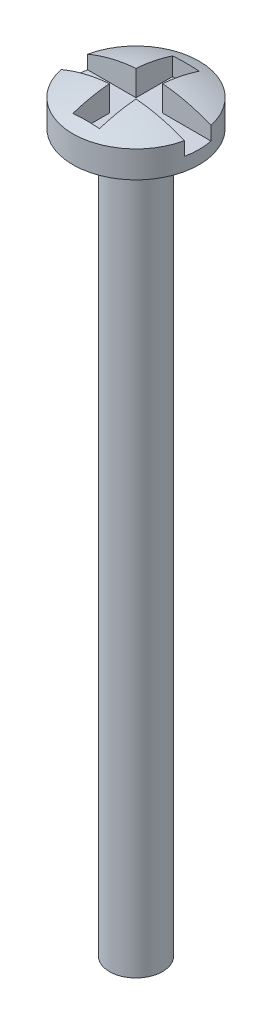
SolidWorks part; units mm, degrees
ref_plane "前视基准面" through (0, 0, 0) normal (0, 0, 1) x (1, 0, 0)
ref_plane "上视基准面" through (0, 0, 0) normal (0, 1, 0) x (1, 0, 0)
ref_plane "右视基准面" through (0, 0, 0) normal (1, 0, 0) x (0, 0, -1)
sketch "草图1" plane through (0, 0, 0) normal (0, 1, 0) x (1, 0, 0)
  circle A0 centre (0, 0) radius 1
  dimension "D1" = 2
extrude "拉伸1" add sketch "草图1" along normal blind 27
sketch "草图2" plane through (0, 27, 0) normal (0, 1, 0) x (-1, 0, 0)
  circle A0 centre (0, 0) radius 2.375
  dimension "D1" = 4.75
extrude "拉伸2" add sketch "草图2" along normal blind 1.5
sketch "草图3" plane through (0, 28.5, 0) normal (0, 1, 0) x (-1, 0, 0)
  line L0 (4.0624, 0) -> (-4.2778, 0) construction
  line L1 (0, -3.5166) -> (0, 3.738) construction
  line L3 (3.5023, -0.5) -> (-3.5023, -0.5)
  line L4 (3.5023, -0.5) -> (3.5023, 0.5)
  line L5 (3.5023, 0.5) -> (-3.5023, 0.5)
  line L6 (-3.5023, -0.5) -> (-3.5023, 0.5)
  dimension "D1" = 1
extrude "切除-拉伸1" cut sketch "草图3" against normal blind 1
sketch "草图4" plane through (0, 28.5, 0) normal (0, 1, 0) x (-1, 0, 0)
  line L0 (0, -3.8639) -> (0, 3.6765) construction
  line L1 (1.7727, 0) -> (-1.7019, 0) construction
  line L2 (0.5, -1.875) -> (-0.5, -1.875)
  line L3 (0.5, -1.875) -> (0.5, 1.875)
  line L4 (0.5, 1.875) -> (-0.5, 1.875)
  line L5 (-0.5, -1.875) -> (-0.5, 1.875)
  dimension "D1" = 1
  dimension "D2" = 3.75
extrude "切除-拉伸2" cut sketch "草图4" against normal blind 1
sketch "草图5" plane through (0, 0, 0) normal (1, 0, 0) x (0, 0, -1)
  line L0 (0, -2.1059) -> (0, 31.9492) construction
  line L1 (-0.5, 28.5) -> (-2.375, 28.5) construction
  line L2 (0, 31.9492) -> (-3.4952, 31.9492)
  line L3 (-3.4952, 27.3768) -> (-3.4952, 31.9492)
  line L5 (0, 31.9492) -> (0, 28.5)
  arc A2 (0, 28.5) -> (-3.4952, 27.3768) centre (0, 22.5) ccw
  dimension "D1" = 6
revolve "切除-旋转16" cut sketch "草图5" angle 360 about L0
